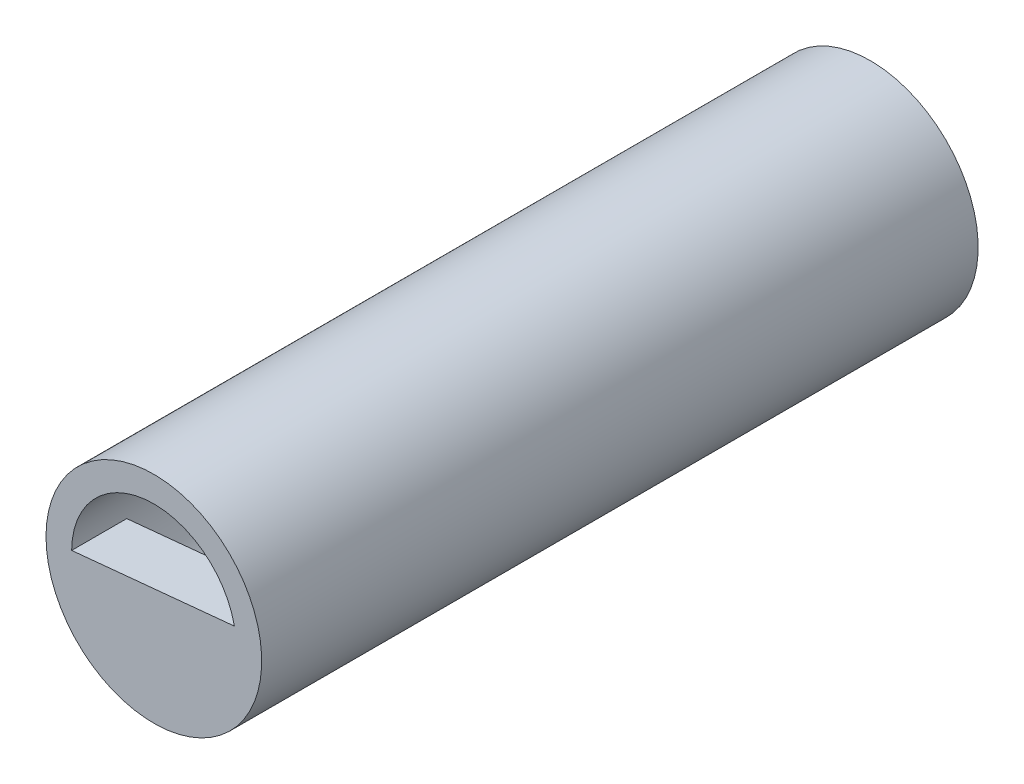
SolidWorks part; units mm, degrees
ref_plane "Front Plane" through (0, 0, 0) normal (0, 0, 1) x (1, 0, 0)
ref_plane "Top Plane" through (0, 0, 0) normal (0, 1, 0) x (1, 0, 0)
ref_plane "Right Plane" through (0, 0, 0) normal (1, 0, 0) x (0, 0, -1)
sketch "Sketch1" plane through (0, 0, 0) normal (0, 0, 1) x (1, 0, 0)
  circle A0 centre (0, 0) radius 37.8964
  circle A1 centre (0, 0) radius 49.7047
extrude "Boss-Extrude1" add sketch "Sketch1" along normal blind 304.8
sketch "Sketch2" plane through (0, 0, 0) normal (0, 0, -1) x (-1, 0, 0)
  circle A0 centre (0, 0) radius 49.7047
extrude "Boss-Extrude2" add sketch "Sketch2" along normal blind 25.4
sketch "Sketch3" plane through (0, 0, 304.8) normal (0, 0, 1) x (1, 0, 0)
  line L0 (44.4075, 8.3565) -> (-41.4368, 0)
  circle A1 centre (0, 0) radius 49.7047
  circle A2 centre (0, 0) radius 49.7047
  circle M3 centre (0, 0) radius 37.8964
  dimension "D1" = 0
extrude "Boss-Extrude3" add sketch "Sketch3" against normal blind 25.4 contours L0 M3
